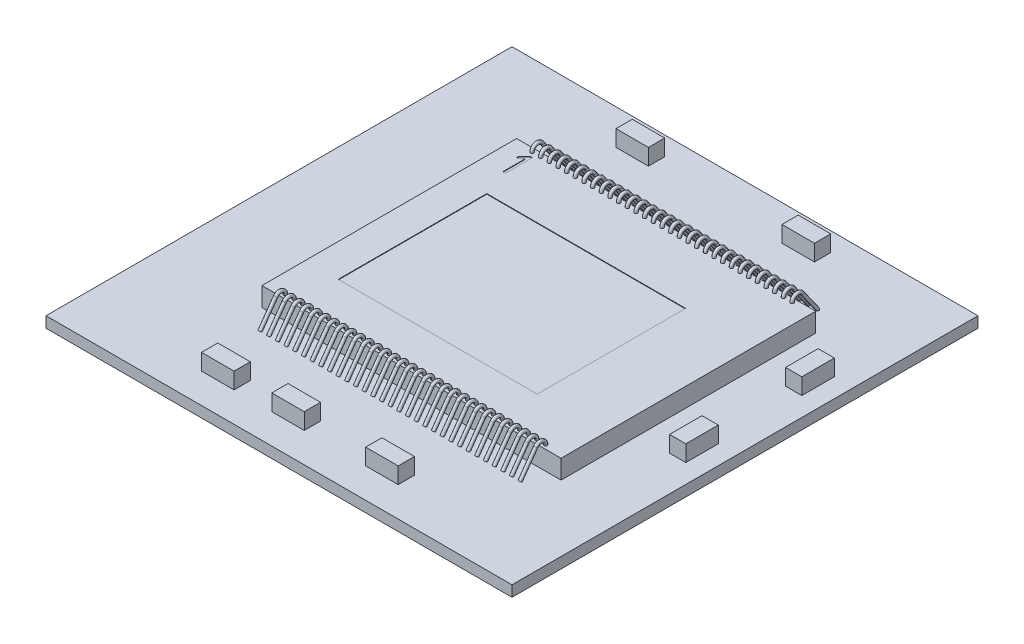
SolidWorks part; units mm, degrees
material "1060 Legierung"
ref_plane "Vorne" through (0, 0, 0) normal (0, 0, 1) x (1, 0, 0)
ref_plane "Oben" through (0, 0, 0) normal (0, 1, 0) x (1, 0, 0)
ref_plane "Rechts" through (0, 0, 0) normal (1, 0, 0) x (0, 0, -1)
ref_plane "Faser-Ebene_Vorne" through (0, 0, 0.175) normal (0, 0, 1) x (1, 0, 0)
ref_plane "Faser-Ebene_Rechts" through (-0.32, 0, 0) normal (1, 0, 0) x (0, 0, -1)
sketch "Skizze1" plane through (0, 0, 0) normal (0, 1, 0) x (1, 0, 0)
  line L0 (-2.76, 2.35) -> (2.76, -2.35) construction
  line L1 (-2.76, 2.35) -> (2.76, 2.35)
  line L2 (-2.76, 2.35) -> (-2.76, -2.35)
  line L3 (-2.76, -2.35) -> (2.76, -2.35)
  line L4 (2.76, 2.35) -> (2.76, -2.35)
  dimension "D1" = 5.52
  dimension "D2" = 4.7
extrude "Chip_Die" add sketch "Skizze1" along normal blind 0.35
sketch "Skizze4" plane through (0, 0.35, 0) normal (0, 1, 0) x (1, 0, 0)
  line L1 (-2.155, 1.195) -> (1.515, 1.195)
  line L2 (-2.155, 1.195) -> (-2.155, -1.545)
  line L3 (-2.155, -1.545) -> (1.515, -1.545)
  line L4 (1.515, 1.195) -> (1.515, -1.545)
  line L5 (-0.32, 1.195) -> (-0.32, -0.1113) construction
  line L7 (-0.32, -0.1925) -> (-0.32, 0.1925) construction
  line L8 (1.515, -0.175) -> (0.7734, -0.175) construction
  line L9 (-0.1925, -0.175) -> (0.1925, -0.175) construction
  dimension "D1" = 3.67
  dimension "D2" = 2.74
extrude "Active_Area" cut sketch "Skizze4" against normal blind 0.01
sketch "Skizze5" plane through (0, 0.35, 0) normal (0, 1, 0) x (1, 0, 0)
  text T0 "1" font "ISOCPEUR" height 0.5
extrude "Pin1" cut sketch "Skizze5" against normal blind 0.01
sketch "Skizze6" plane through (0, 0, 0) normal (0, 1, 0) x (1, 0, 0)
  line L0 (-2.155, 1.195) -> (1.515, -1.545) construction
  line L1 (-4.62, 4.125) -> (3.98, 4.125)
  line L2 (-4.62, 4.125) -> (-4.62, -4.475)
  line L3 (-4.62, -4.475) -> (3.98, -4.475)
  line L4 (3.98, 4.125) -> (3.98, -4.475)
  line L5 (3.98, 4.125) -> (-4.62, -4.475) construction
  point P7 (-0.32, -0.175)
  dimension "D1" = 8.6
extrude "Base-Plate" add sketch "Skizze6" against normal blind 0.2
sketch "Skizze12" plane through (0, 0, 0) normal (1, 0, 0) x (0, 0, -1)
  line L0 (-2.35, 0.35) -> (2.35, 0.35) construction
  line L1 (-2.4563, 0.4079) -> (-2.7458, 0)
  line L2 (-4.475, 0) -> (4.125, 0) construction
  line L3 (0, 0) -> (0, 1.1196) construction
  arc A0 (-2.2748, 0.35) -> (-2.4563, 0.4079) centre (-2.3748, 0.35) ccw
  dimension "D1" = 0.1
sketch "Skizze13" plane through (0, 0.35, 0) normal (0, 1, 0) x (1, 0, 0)
  line L0 (0, 0) -> (0, -1.1473) construction
  circle A0 centre (0, -2.2748) radius 0.03
  circle A1 centre (0.16, -2.2748) radius 0.03
  circle A2 centre (0.32, -2.2748) radius 0.03
  circle A3 centre (0.48, -2.2748) radius 0.03
  circle A4 centre (0.64, -2.2748) radius 0.03
  circle A5 centre (0.8, -2.2748) radius 0.03
  circle A6 centre (0.96, -2.2748) radius 0.03
  circle A7 centre (1.12, -2.2748) radius 0.03
  circle A8 centre (1.28, -2.2748) radius 0.03
  circle A9 centre (1.44, -2.2748) radius 0.03
  circle A10 centre (1.6, -2.2748) radius 0.03
  circle A11 centre (1.76, -2.2748) radius 0.03
  circle A12 centre (1.92, -2.2748) radius 0.03
  circle A13 centre (2.08, -2.2748) radius 0.03
  circle A14 centre (2.24, -2.2748) radius 0.03
  circle A15 centre (2.4, -2.2748) radius 0.03
  circle A16 centre (-2.4, -2.2748) radius 0.03
  circle A17 centre (-2.24, -2.2748) radius 0.03
  circle A18 centre (-2.08, -2.2748) radius 0.03
  circle A19 centre (-1.92, -2.2748) radius 0.03
  circle A20 centre (-1.76, -2.2748) radius 0.03
  circle A21 centre (-1.6, -2.2748) radius 0.03
  circle A22 centre (-1.44, -2.2748) radius 0.03
  circle A23 centre (-1.28, -2.2748) radius 0.03
  circle A24 centre (-1.12, -2.2748) radius 0.03
  circle A25 centre (-0.96, -2.2748) radius 0.03
  circle A26 centre (-0.8, -2.2748) radius 0.03
  circle A27 centre (-0.64, -2.2748) radius 0.03
  circle A28 centre (-0.48, -2.2748) radius 0.03
  circle A29 centre (-0.32, -2.2748) radius 0.03
  circle A30 centre (-0.16, -2.2748) radius 0.03
  dimension "D1" = 0.06
  dimension "D2" = 16
sweep "Bonding-wires" add profiles "Skizze13" path "Skizze12"
mirror "Spiegeln1" about plane through (0, 0, 0) normal (0, 0, 1) of "Bonding-wires"
sketch "Skizze14" plane through (0, 0, 0) normal (0, 1, 0) x (1, 0, 0)
  line L0 (-4.62, -4.475) -> (3.98, -4.475) construction
  line L1 (-2.2994, -3.625) -> (-1.6994, -3.625)
  line L2 (-2.2994, -3.625) -> (-2.2994, -3.925)
  line L3 (-2.2994, -3.925) -> (-1.6994, -3.925)
  line L4 (-1.6994, -3.625) -> (-1.6994, -3.925)
  line L5 (3.98, -4.475) -> (3.98, 4.125) construction
  line L6 (-1.0036, -3.625) -> (-0.4036, -3.625)
  line L7 (-1.0036, -3.625) -> (-1.0036, -3.925)
  line L8 (-1.0036, -3.925) -> (-0.4036, -3.925)
  line L9 (-0.4036, -3.625) -> (-0.4036, -3.925)
  line L10 (0.7291, -3.925) -> (1.3291, -3.925)
  line L11 (0.7291, -3.925) -> (0.7291, -3.625)
  line L12 (0.7291, -3.625) -> (1.3291, -3.625)
  line L13 (1.3291, -3.925) -> (1.3291, -3.625)
  line L14 (3.33, -0.3181) -> (3.63, -0.3181)
  line L15 (3.33, -0.3181) -> (3.33, -0.9181)
  line L16 (3.33, -0.9181) -> (3.63, -0.9181)
  line L17 (3.63, -0.3181) -> (3.63, -0.9181)
  line L18 (3.98, 4.125) -> (-4.62, 4.125) construction
  line L19 (3.33, 1.2236) -> (3.63, 1.2236)
  line L20 (3.33, 1.2236) -> (3.33, 1.8236)
  line L21 (3.33, 1.8236) -> (3.63, 1.8236)
  line L22 (3.63, 1.2236) -> (3.63, 1.8236)
  line L23 (-1.4515, 3.475) -> (-2.0515, 3.475)
  line L24 (-1.4515, 3.475) -> (-1.4515, 3.775)
  line L25 (-1.4515, 3.775) -> (-2.0515, 3.775)
  line L26 (-2.0515, 3.475) -> (-2.0515, 3.775)
  line L28 (1.012, 3.775) -> (1.612, 3.775)
  line L29 (1.012, 3.775) -> (1.012, 3.475)
  line L30 (1.012, 3.475) -> (1.612, 3.475)
  line L31 (1.612, 3.775) -> (1.612, 3.475)
  dimension "D1" = 0.3
  dimension "D2" = 0.6
  dimension "D3" = 0.55
  dimension "D4" = 0.35
  dimension "D5" = 0.35
extrude "Electronic_components" add sketch "Skizze14" along normal blind 0.3
